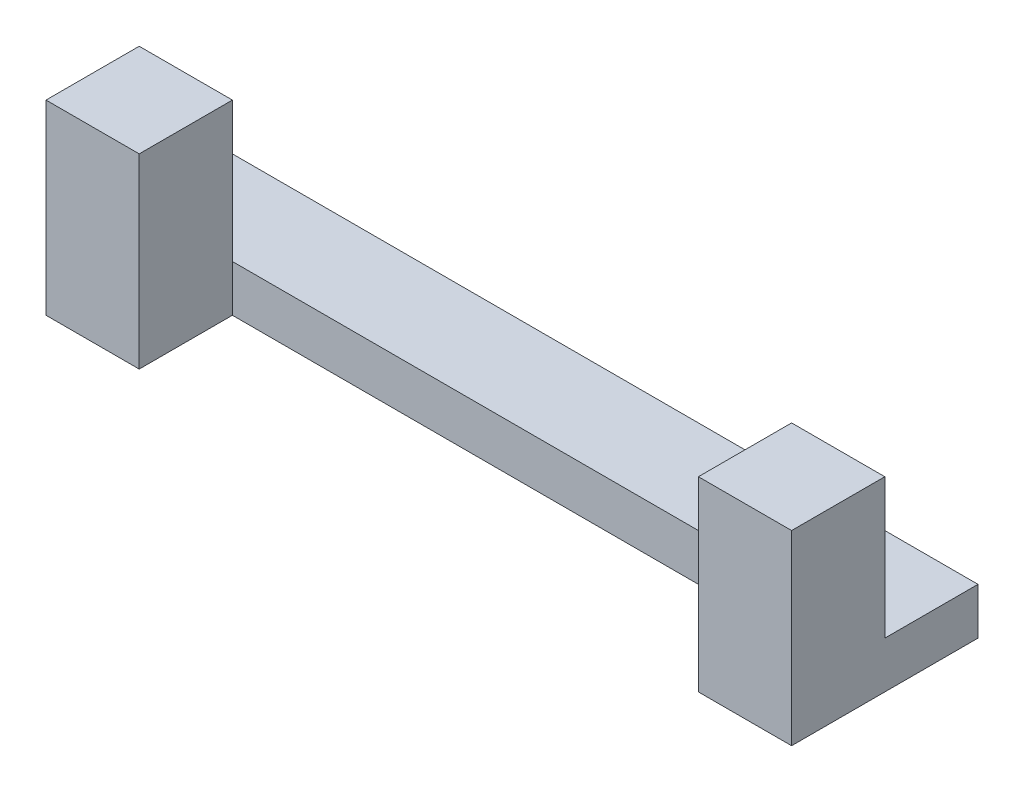
SolidWorks part; units mm, degrees
ref_plane "Front Plane" through (0, 0, 0) normal (0, 0, 1) x (1, 0, 0)
ref_plane "Top Plane" through (0, 0, 0) normal (0, 1, 0) x (1, 0, 0)
ref_plane "Right Plane" through (0, 0, 0) normal (1, 0, 0) x (0, 0, -1)
sketch "Sketch1" plane through (0, 0, 0) normal (0, 1, 0) x (1, 0, 0)
  line L1 (-100, -12.5) -> (100, -12.5)
  line L2 (-100, -12.5) -> (-100, 12.5)
  line L3 (-100, 12.5) -> (100, 12.5)
  line L4 (100, -12.5) -> (100, 12.5)
  line L5 (-100, -12.5) -> (100, 12.5) construction
  line L6 (-100, 12.5) -> (100, -12.5) construction
  point P0 (0, 0)
  dimension "D1" = 200
  dimension "D2" = 25
extrude "Boss-Extrude3" add sketch "Sketch1" along normal blind 12.5 contours L3 L4 L1 L2
sketch "Sketch2" plane through (0, 0, 0) normal (0, 1, 0) x (1, 0, 0)
  line L1 (-100, -12.5) -> (-75, -12.5)
  line L2 (-100, -12.5) -> (-100, -37.5)
  line L3 (-100, -37.5) -> (-75, -37.5)
  line L4 (-75, -12.5) -> (-75, -37.5)
  line L5 (100, -12.5) -> (75, -12.5)
  line L6 (100, -12.5) -> (100, -37.5)
  line L7 (100, -37.5) -> (75, -37.5)
  line L8 (75, -12.5) -> (75, -37.5)
  dimension "D1" = 25
  dimension "D2" = 25
  dimension "D3" = 25
  dimension "D4" = 25
extrude "Boss-Extrude4" add sketch "Sketch2" along normal blind 50
